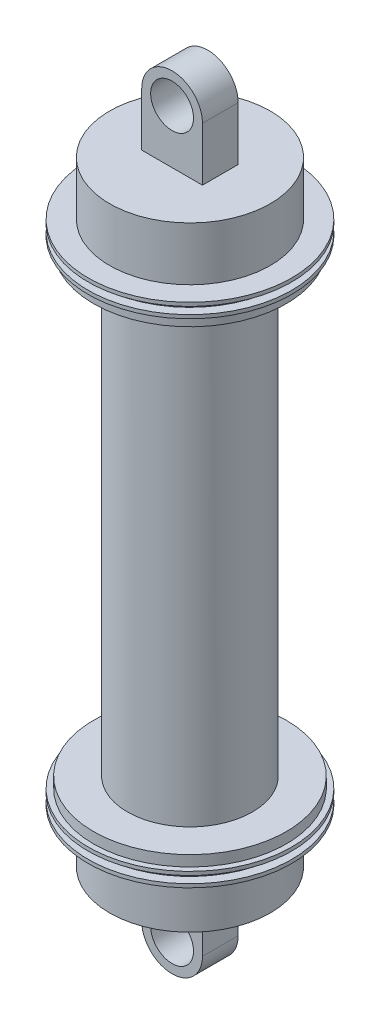
SolidWorks part; units mm, degrees
ref_plane "Front Plane" through (0, 0, 0) normal (0, 0, 1) x (1, 0, 0)
ref_plane "Top Plane" through (0, 0, 0) normal (0, 1, 0) x (1, 0, 0)
ref_plane "Right Plane" through (0, 0, 0) normal (1, 0, 0) x (0, 0, -1)
sketch "Sketch1" plane through (0, 0, 0) normal (0, 1, 0) x (1, 0, 0)
  circle A0 centre (0, 0) radius 17.5
  dimension "D1" = 35
extrude "Boss-Extrude1" add sketch "Sketch1" along normal blind 142
shell "Shell1" thickness 2
sketch "Sketch2" plane through (0, 0, 0) normal (0, -1, 0) x (1, 0, 0)
  circle A0 centre (0, 0) radius 22.5
  dimension "D1" = 45
extrude "Boss-Extrude2" add sketch "Sketch2" along normal blind 15
sketch "Sketch3" plane through (0, 0, 0) normal (0, 0, 1) x (1, 0, 0)
  line L0 (0, 0) -> (0, -41.4272) construction
  line L1 (-8.5, -15) -> (-8.5, -30)
  line L2 (-22.5, -15) -> (22.5, -15) construction
  line L3 (8.5, -30) -> (8.5, -15)
  line L4 (-8.5, -15) -> (8.5, -15)
  arc A0 (-8.5, -30) -> (8.5, -30) centre (0, -30) ccw
  circle A1 centre (0, -30) radius 6
  dimension "D1" = 12
  dimension "D2" = 2.5
  dimension "D3" = 15
extrude "Boss-Extrude3" add sketch "Sketch3" along normal mid plane 10
ref_plane "Plane1" through (0, 71, 0) normal (0, 1, 0) x (1, 0, 0)
mirror "Mirror1" about plane through (0, 71, 0) normal (0, 1, 0) of "Boss-Extrude2", "Boss-Extrude3"
sketch "Sketch4" plane through (0, 142, 0) normal (0, -1, 0) x (1, 0, 0)
  circle A0 centre (0, 0) radius 28.5
  dimension "D1" = 57
extrude "Boss-Extrude4" add sketch "Sketch4" along normal blind 1
sketch "Sketch5" plane through (0, 141, 0) normal (0, -1, 0) x (1, 0, 0)
  circle A0 centre (0, 0) radius 26
  dimension "D1" = 52
extrude "Boss-Extrude5" add sketch "Sketch5" along normal blind 2
sketch "Sketch6" plane through (0, 139, 0) normal (0, -1, 0) x (1, 0, 0)
  circle A0 centre (0, 0) radius 28.5
  dimension "D1" = 57
extrude "Boss-Extrude6" add sketch "Sketch6" along normal blind 1
ref_plane "Plane2" through (0, 71, 0) normal (0, 1, 0) x (1, 0, 0)
mirror "Mirror2" about plane through (0, 71, 0) normal (0, 1, 0) of "Boss-Extrude4", "Boss-Extrude5", "Boss-Extrude6"
sketch "Sketch7" plane through (0, 138, 0) normal (0, -1, 0) x (1, 0, 0)
  circle A0 centre (0, 0) radius 27
  dimension "D1" = 54
extrude "Boss-Extrude7" add sketch "Sketch7" along normal blind 3
mirror "Mirror3" about plane through (0, 71, 0) normal (0, 1, 0) of "Boss-Extrude7"
